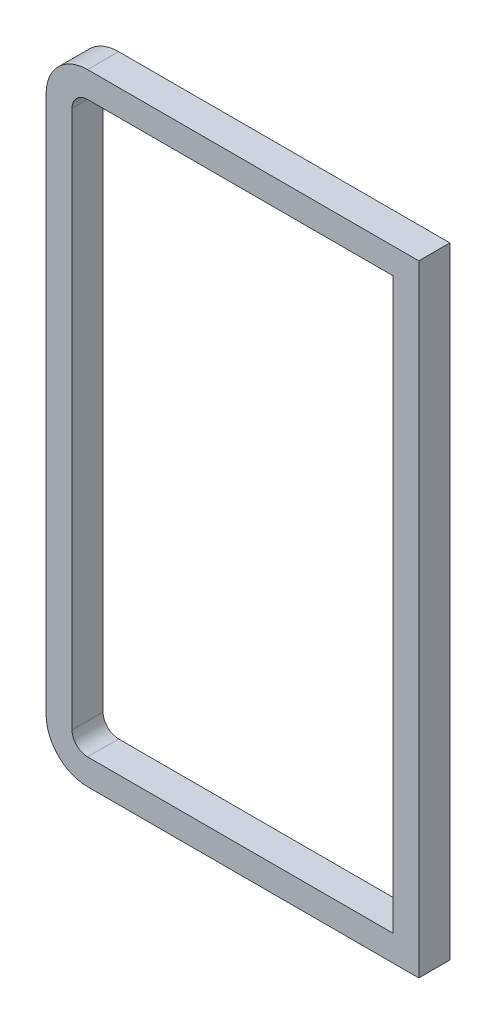
SolidWorks part; units mm, degrees
ref_plane "Front Plane" through (0, 0, 0) normal (0, 0, 1) x (1, 0, 0)
ref_plane "Top Plane" through (0, 0, 0) normal (0, 1, 0) x (1, 0, 0)
ref_plane "Right Plane" through (0, 0, 0) normal (1, 0, 0) x (0, 0, -1)
sketch "Sketch1" plane through (0, 0, 0) normal (0, 0, 1) x (1, 0, 0)
  line L1 (101.6, 0) -> (914.4, 0)
  line L2 (0, 101.6) -> (0, 1422.4)
  line L3 (101.6, 1524) -> (914.4, 1524)
  line L4 (914.4, 0) -> (914.4, 1524)
  arc A0 (101.6, 0) -> (0, 101.6) centre (101.6, 101.6) cw
  arc A1 (0, 1422.4) -> (101.6, 1524) centre (101.6, 1422.4) cw
  point P7 (0, 0)
  point P10 (0, 1524)
  dimension "D3" = 101.6
  dimension "D1" = 914.4
  dimension "D2" = 1524
extrude "Boss-Extrude1" add sketch "Sketch1" along normal blind 76.2
sketch "Sketch2" plane through (0, 0, 76.2) normal (0, 0, 1) x (1, 0, 0)
  line L0 (63.5, 1422.4) -> (63.5, 101.6)
  line L1 (101.6, 63.5) -> (850.9, 63.5)
  line L2 (850.9, 63.5) -> (850.9, 1460.5)
  line L3 (850.9, 1460.5) -> (101.6, 1460.5)
  arc A0 (63.5, 101.6) -> (101.6, 63.5) centre (101.6, 101.6) ccw
  arc A1 (101.6, 1460.5) -> (63.5, 1422.4) centre (101.6, 1422.4) ccw
extrude "Cut-Extrude2" cut sketch "Sketch2" against normal through all
